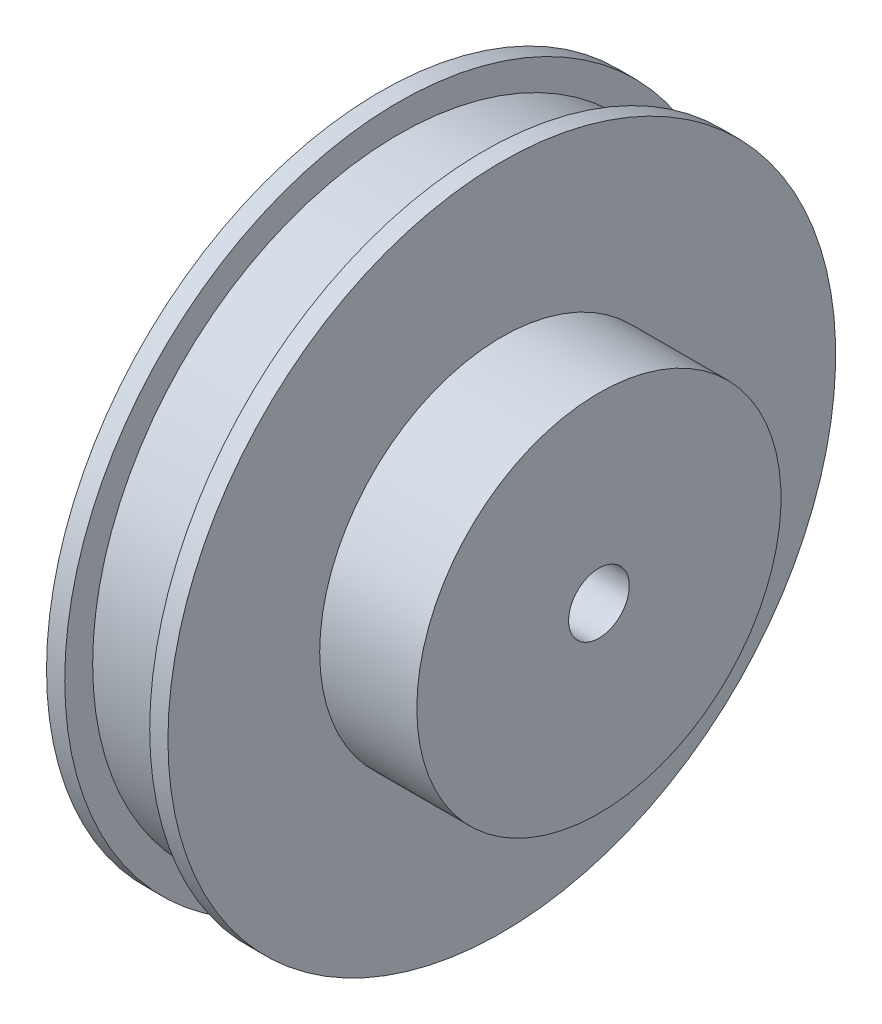
SolidWorks part; units mm, degrees
material "6061-T6 (SS)"
ref_plane "Front Plane" through (0, 0, 0) normal (0, 0, 1) x (1, 0, 0)
ref_plane "Top Plane" through (0, 0, 0) normal (0, 1, 0) x (1, 0, 0)
ref_plane "Right Plane" through (0, 0, 0) normal (1, 0, 0) x (0, 0, -1)
sketch "Sketch1" plane through (0, 0, 0) normal (0, 0, 1) x (1, 0, 0)
  line L0 (-19.682, 0) -> (-3.2295, 0) construction
  line L1 (0, 2.5) -> (0, 27.5)
  line L2 (0, 27.5) -> (1.5, 27.5)
  line L3 (1.5, 27.5) -> (1.5, 25.2)
  line L4 (1.5, 25.2) -> (8.5, 25.2)
  line L5 (8.5, 25.2) -> (8.5, 27.5)
  line L6 (8.5, 27.5) -> (10, 27.5)
  line L7 (10, 27.5) -> (10, 15)
  line L8 (10, 15) -> (18, 15)
  line L9 (18, 15) -> (18, 2.5)
  line L11 (0, 2.5) -> (18, 2.5)
  dimension "D1" = 1.5
  dimension "D2" = 55
  dimension "D3" = 50.4
  dimension "D4" = 7
  dimension "D5" = 5
  dimension "D6" = 18
  dimension "D7" = 30
revolve "Revolve1" add sketch "Sketch1" angle 360 about L0
